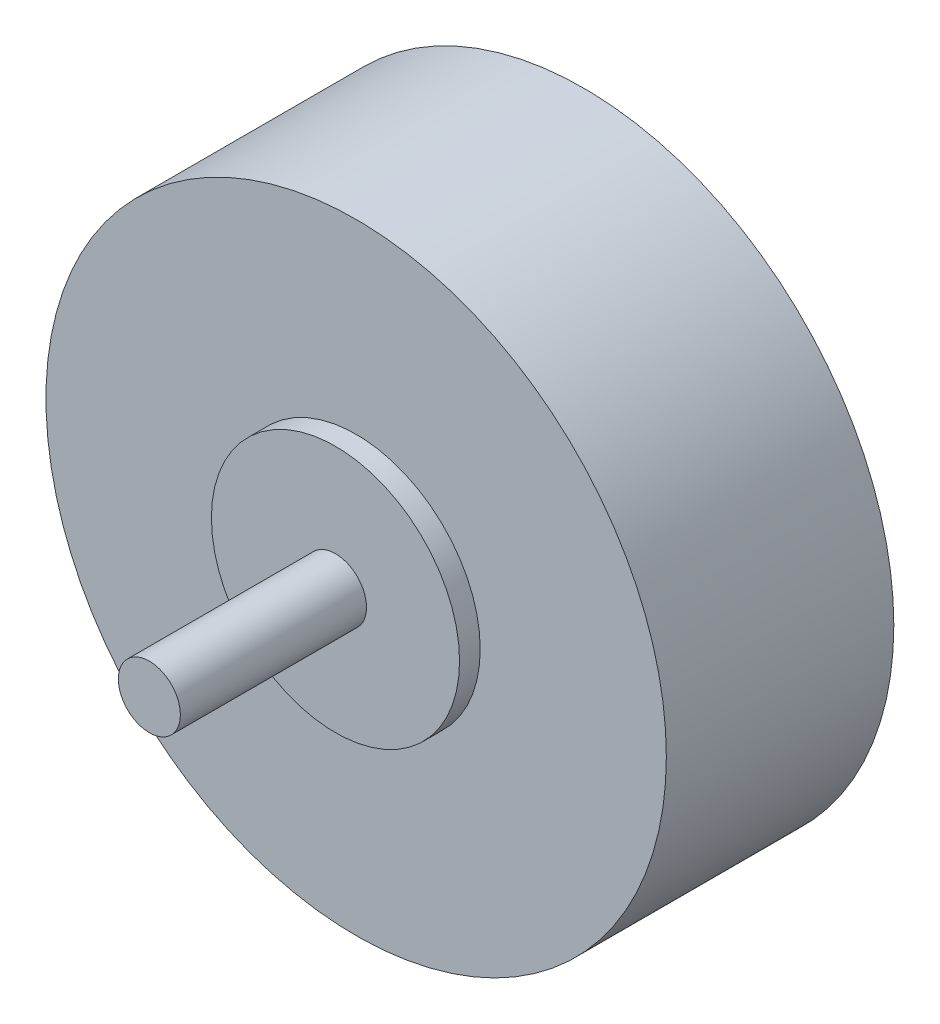
SolidWorks part; units mm, degrees
ref_plane "Plan de face" through (0, 0, 0) normal (0, 0, 1) x (1, 0, 0)
ref_plane "Plan de dessus" through (0, 0, 0) normal (0, 1, 0) x (1, 0, 0)
ref_plane "Plan de droite" through (0, 0, 0) normal (1, 0, 0) x (0, 0, -1)
sketch "Esquisse1" plane through (0, 0, 0) normal (0, 0, 1) x (1, 0, 0)
  circle A0 centre (0, 0) radius 7.5
  dimension "D1" = 15
extrude "Boss.-Extru.1" add sketch "Esquisse1" along normal blind 5.5
sketch "Esquisse2" plane through (0, 0, 5.5) normal (0, 0, 1) x (1, 0, 0)
  circle A0 centre (0, 0) radius 3
  circle A1 centre (0, 0) radius 7.5 construction
  dimension "D1" = 6
extrude "Boss.-Extru.2" add sketch "Esquisse2" along normal blind 0.5
sketch "Esquisse3" plane through (0, 0, 6) normal (0, 0, 1) x (1, 0, 0)
  circle A0 centre (0, 0) radius 0.75
  dimension "D1" = 1.5
extrude "Boss.-Extru.3" add sketch "Esquisse3" along normal blind 4.5
sketch "Esquisse4" plane through (0, 0, 0) normal (0, 0, -1) x (-1, 0, 0)
  circle A0 centre (0, 0) radius 2
  dimension "D1" = 4
extrude "Boss.-Extru.4" add sketch "Esquisse4" along normal blind 1.4
sketch "Esquisse5" plane through (0, 0, 0) normal (0, 0, -1) x (-1, 0, 0)
  circle A0 centre (0, 0) radius 0.75
  dimension "D1" = 1.5
extrude "Boss.-Extru.5" add sketch "Esquisse5" along normal blind 4
